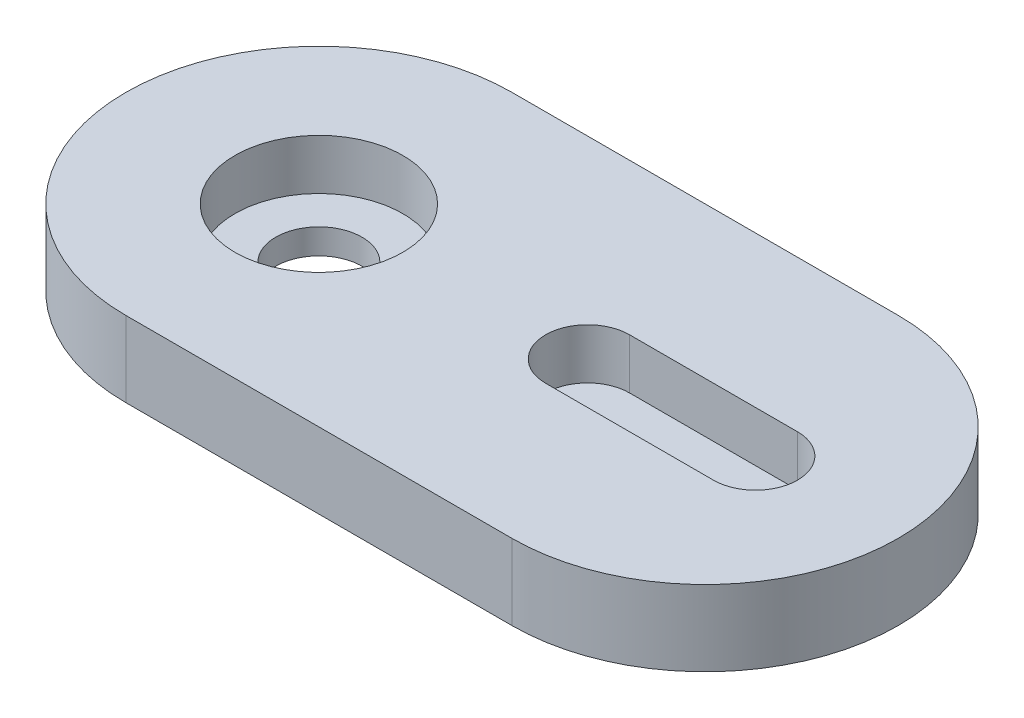
SolidWorks part; units mm, degrees
ref_plane "Front Plane" through (0, 0, 0) normal (0, 0, 1) x (1, 0, 0)
ref_plane "Top Plane" through (0, 0, 0) normal (0, 1, 0) x (1, 0, 0)
ref_plane "Right Plane" through (0, 0, 0) normal (1, 0, 0) x (0, 0, -1)
sketch "Sketch1" plane through (0, 0, 0) normal (0, 1, 0) x (1, 0, 0)
  line L0 (0, 0) -> (7.3025, 0) construction
  line L1 (14.605, 7.3025) -> (0, 7.3025)
  line L2 (14.605, -7.3025) -> (0, -7.3025)
  line L3 (21.9075, 0) -> (30.4224, 0) construction
  arc A0 (0, 7.3025) -> (0, -7.3025) centre (0, 0) ccw
  arc A1 (14.605, -7.3025) -> (14.605, 7.3025) centre (14.605, 0) ccw
  dimension "D1" = 14.605
  dimension "D2" = 14.605
  dimension "D3" = 14.605
extrude "Boss-Extrude1" add sketch "Sketch1" along normal blind 2.8575
sketch "Sketch2" plane through (0, 2.8575, 0) normal (0, 1, 0) x (1, 0, 0)
  circle A0 centre (0, 0) radius 1.632
  dimension "D1" = 3.2639
extrude "Cut-Extrude1" cut sketch "Sketch2" against normal blind 3.048
sketch "Sketch3" plane through (0, 2.8575, 0) normal (0, 1, 0) x (1, 0, 0)
  line L0 (10.16, 1.5875) -> (16.51, 1.5875)
  line L1 (10.16, -1.5875) -> (16.51, -1.5875)
  arc A0 (16.51, -1.5875) -> (16.51, 1.5875) centre (16.51, 0) ccw
  arc A1 (10.16, 1.5875) -> (10.16, -1.5875) centre (10.16, 0) ccw
  circle A2 centre (0, 0) radius 3.175
  dimension "D1" = 3.175
  dimension "D2" = 3.175
  dimension "D5" = 6.35
  dimension "D3" = 6.35
  dimension "D4" = 10.16
extrude "Cut-Extrude2" cut sketch "Sketch3" against normal blind 1.905
